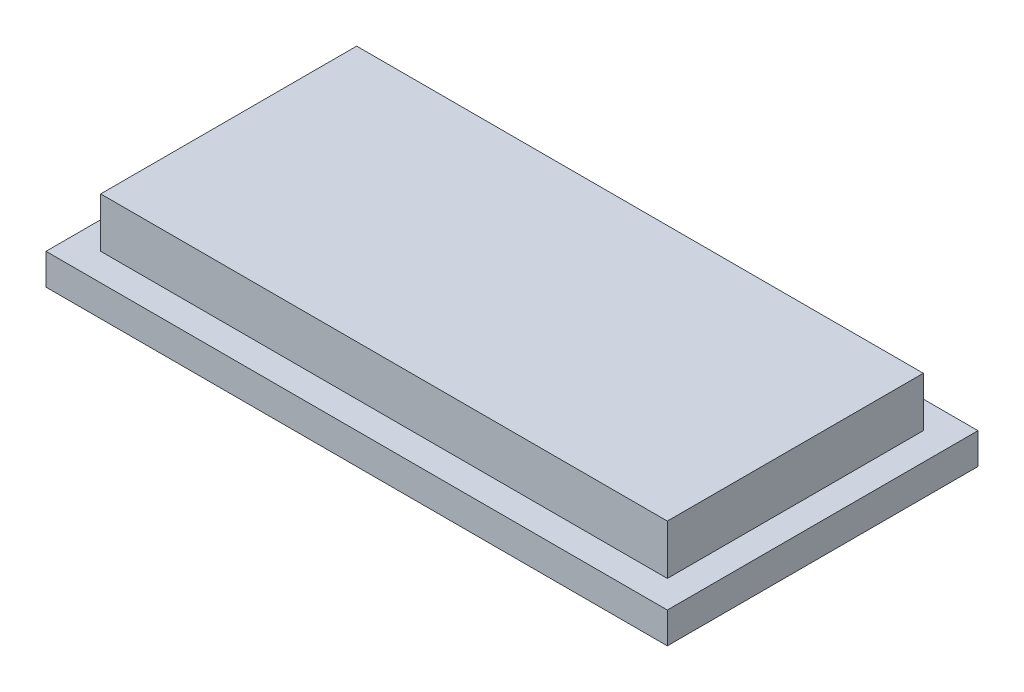
SolidWorks part; units mm, degrees
ref_plane "Front Plane" through (0, 0, 0) normal (0, 0, 1) x (1, 0, 0)
ref_plane "Top Plane" through (0, 0, 0) normal (0, 1, 0) x (1, 0, 0)
ref_plane "Right Plane" through (0, 0, 0) normal (1, 0, 0) x (0, 0, -1)
sketch "Sketch1" plane through (0, 0, 0) normal (0, 1, 0) x (1, 0, 0)
  line L1 (0, 0) -> (50, 0)
  line L2 (0, 0) -> (0, 25)
  line L3 (0, 25) -> (50, 25)
  line L4 (50, 0) -> (50, 25)
  dimension "D1" = 50
  dimension "D2" = 25
extrude "Boss-Extrude1" add sketch "Sketch1" along normal blind 2.5
sketch "Sketch2" plane through (0, 2.5, 0) normal (0, 1, 0) x (1, 0, 0)
  line L9 (2.2, 2.2) -> (47.8, 2.2)
  line L10 (2.2, 2.2) -> (2.2, 22.8)
  line L11 (2.2, 22.8) -> (47.8, 22.8)
  line L12 (47.8, 2.2) -> (47.8, 22.8)
extrude "Boss-Extrude2" add sketch "Sketch2" along normal blind 4
